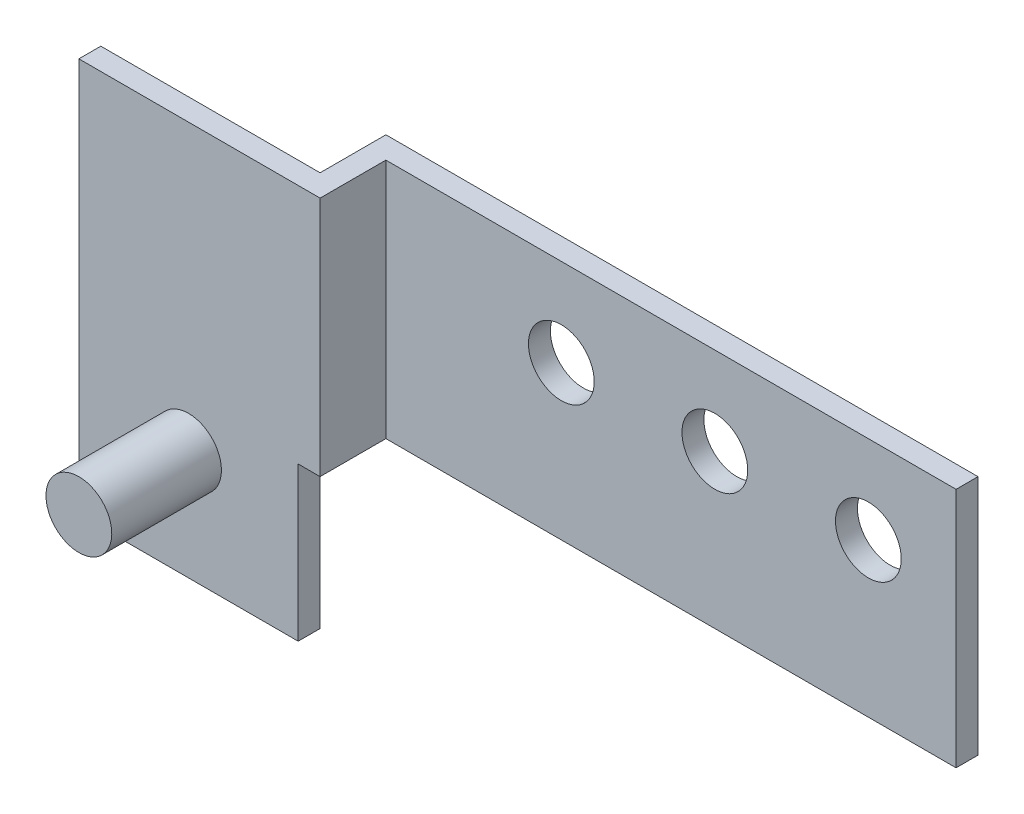
SolidWorks part; units mm, degrees
material "Обычная углеродистая сталь"
ref_plane "Спереди" through (0, 0, 0) normal (0, 0, 1) x (1, 0, 0)
ref_plane "Сверху" through (0, 0, 0) normal (0, 1, 0) x (1, 0, 0)
ref_plane "Справа" through (0, 0, 0) normal (1, 0, 0) x (0, 0, -1)
ref_plane "Плоскость4" through (0, 0, 4) normal (0, 0, 1) x (1, 0, 0)
sketch "Эскиз1" plane through (0, 0, 4) normal (0, 0, 1) x (1, 0, 0)
  line L0 (-10, -18) -> (27, -18)
  line L1 (27, -18) -> (27, 0)
  line L2 (27, 0) -> (-10, 0)
  line L3 (-10, 0) -> (-10, -18)
extrude "Бобышка-Вытянуть1" add sketch "Эскиз1" against normal blind 1
sketch "Эскиз2" plane through (0, 0, 4) normal (0, 0, 1) x (1, 0, 0)
  line L0 (27, -11) -> (0, -11)
  line L1 (0, -11) -> (0, -18)
  line L2 (0, -18) -> (27, -18)
  line L3 (27, -18) -> (27, -11)
extrude "Вырез-Вытянуть1" cut sketch "Эскиз2" against normal through all
sketch "Эскиз3" plane through (0, 0, 3) normal (0, 0, -1) x (-1, 0, 0)
  line L0 (-27, -11) -> (-27, 0)
  line L1 (-27, 0) -> (0, 0)
  line L2 (0, 0) -> (0, -11)
  line L3 (0, -11) -> (-27, -11)
extrude "Бобышка-Вытянуть2" add sketch "Эскиз3" along normal blind 3
sketch "Эскиз4" plane through (0, -11, 0) normal (0, -1, 0) x (1, 0, 0)
  line L0 (1, 4) -> (1, 1)
  line L1 (1, 1) -> (27, 1)
  line L2 (27, 1) -> (27, 4)
  line L3 (27, 4) -> (1, 4)
extrude "Вырез-Вытянуть2" cut sketch "Эскиз4" against normal through all
ref_plane "Плоскость5" through (0, -13, 0) normal (0, -1, 0) x (1, 0, 0)
sketch "Эскиз5" plane through (0, -13, 0) normal (0, -1, 0) x (1, 0, 0)
  line L0 (-3.5, 9) -> (-5, 9)
  line L1 (-5, 9) -> (-5, 4)
  line L2 (-5, 4) -> (-3.5, 4)
  line L3 (-3.5, 4) -> (-3.5, 9)
  line L4 (-5, 9) -> (-5, 4) construction
revolve "Повернуть1" add sketch "Эскиз5" angle 360 about L4
hole_wizard "Диаметр отверстия Ø3.0 (3)1" positions "Эскиз7" profile "Эскиз6" hole size "Ø3.0" standard "Ansi Metric"
sketch "Эскиз7" plane through (0, 0, 1) normal (0, 0, 1) x (1, 0, 0)
  point P0 (23, -4)
  point P1 (16, -4)
  point P2 (9, -4)
sketch "Эскиз6" plane through (23, -4, 1) normal (1, 0, 0) x (0, -1, 0)
  line L0 (0, 0) -> (0, 1)
  line L1 (0, 1) -> (1.5, 1)
  line L2 (1.5, 1) -> (1.5, 0)
  line L5 (1.5, 0) -> (0, 0)
  line L11 (0, -6.35) -> (0, 107.95) construction
  dimension "Диаметр сквозного отверстия" = 3
  dimension "Глубина сквозного отверстия" = 1
